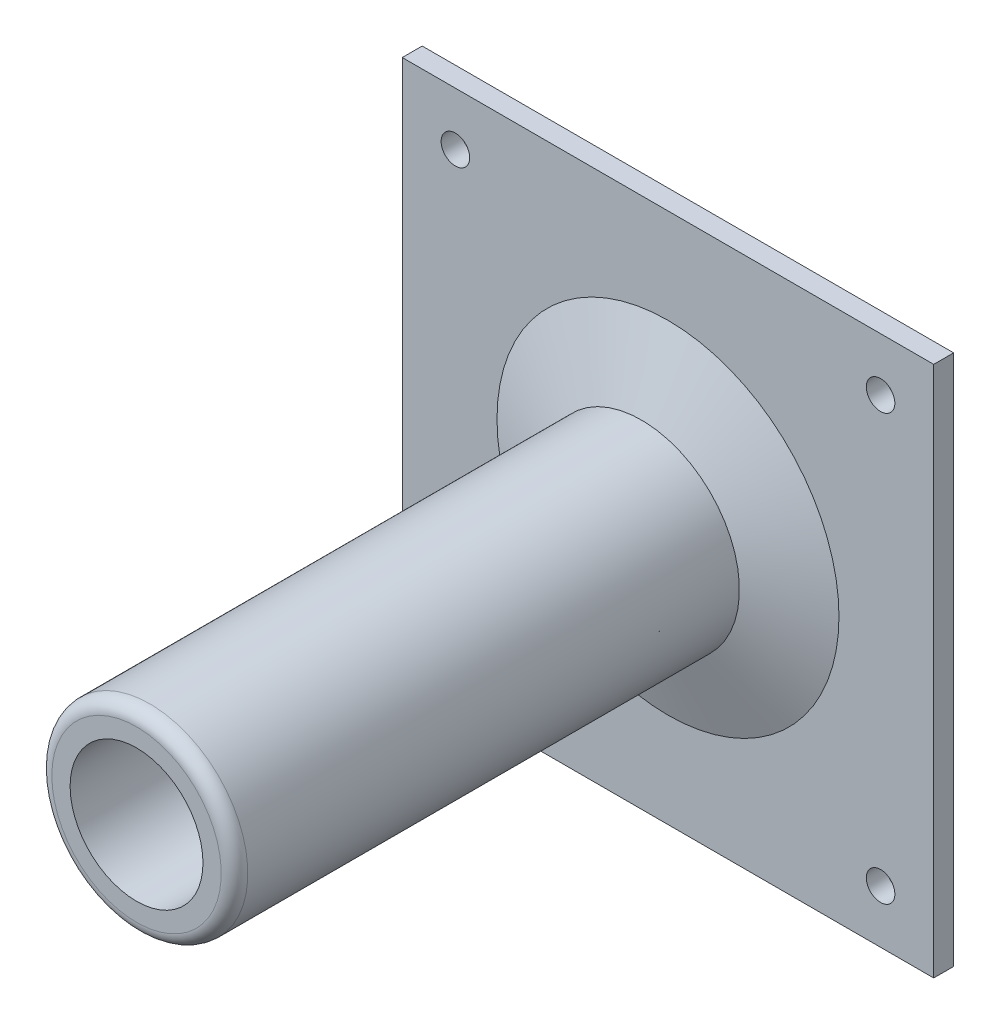
SolidWorks part; units mm, degrees
ref_plane "Plan de face" through (0, 0, 0) normal (0, 0, 1) x (1, 0, 0)
ref_plane "Plan de dessus" through (0, 0, 0) normal (0, 1, 0) x (1, 0, 0)
ref_plane "Plan de droite" through (0, 0, 0) normal (1, 0, 0) x (0, 0, -1)
sketch "Esquisse1" plane through (0, 0, 0) normal (0, 0, 1) x (1, 0, 0)
  line L1 (-40, -40) -> (40, -40)
  line L2 (-40, -40) -> (-40, 40)
  line L3 (-40, 40) -> (40, 40)
  line L4 (40, -40) -> (40, 40)
  line L5 (-40, -40) -> (40, 40) construction
  line L6 (-40, 40) -> (40, -40) construction
  point P0 (0, 0)
  dimension "D1" = 80
  dimension "D2" = 80
extrude "Boss.-Extru.1" add sketch "Esquisse1" along normal blind 3
sketch "Esquisse2" plane through (0, 0, 0) normal (0, 0, 1) x (1, 0, 0)
  circle A0 centre (0, 0) radius 14.75
  dimension "D1" = 29.5
extrude "Boss.-Extru.2" add sketch "Esquisse2" along normal blind 80 from surface at 3 starting at face at (0, 0, 3)
fillet "Congé1" radius 2 1 edges at (-14.75, 0, 83)
chamfer "Chanfrein1" distance 4 angle 70 1 edges at (-14.75, 0, 3)
sketch "Esquisse3" plane through (0, 0, 0) normal (0, 0, 1) x (1, 0, 0)
  circle A0 centre (0, 0) radius 10
  dimension "D1" = 20
extrude "Enlèv. mat.-Extru.1" cut sketch "Esquisse3" along normal through all both and the other way through all
fillet "Congé2" radius 5 1 edges at (-10, 0, 0)
hole_wizard "Dégagement M43" positions "Esquisse8" profile "Esquisse9" hole size "M4" standard "ISO" end condition through all
sketch "Esquisse8" plane through (3.9717, 8.0627, 3) normal (0, 0, 1) x (1, 0, 0)
  point P0 (28.0283, -40.0627)
sketch "Esquisse9" plane through (32, -32, 3) normal (1, 0, 0) x (0, -1, 0)
  line L0 (0, 0) -> (0, 3)
  line L1 (0, 3) -> (2.15, 3)
  line L2 (2.15, 3) -> (2.15, 0)
  line L3 (2.15, 0) -> (0, 0)
  line L4 (0, -6.35) -> (0, 107.95) construction
  dimension "Diamètre du perçage jusqu'au prochain" = 4.3
  dimension "Profondeur du perçage jusqu'au prochain" = 3
mirror "Symétrie1" about plane through (0, 0, 0) normal (0, 1, 0) of "Dégagement M43"
mirror "Symétrie2" about plane through (0, 0, 0) normal (1, 0, 0) of "Symétrie1", "Dégagement M43"
